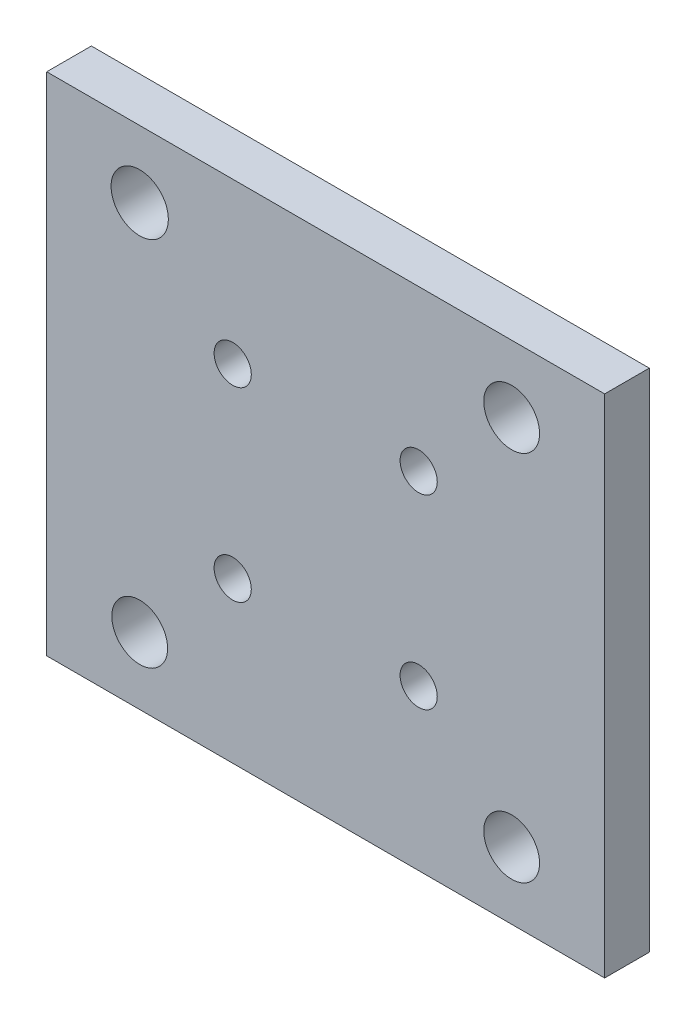
SolidWorks part; units mm, degrees
ref_plane "Front Plane" through (0, 0, 0) normal (0, 0, 1) x (1, 0, 0)
ref_plane "Top Plane" through (0, 0, 0) normal (0, 1, 0) x (1, 0, 0)
ref_plane "Right Plane" through (0, 0, 0) normal (1, 0, 0) x (0, 0, -1)
sketch "Sketch1" plane through (0, 0, 0) normal (0, 0, 1) x (1, 0, 0)
  line L1 (0, 0) -> (75, 0)
  line L2 (0, 0) -> (0, 68)
  line L3 (0, 68) -> (75, 68)
  line L4 (75, 0) -> (75, 68)
  circle A0 centre (12.5, 59) radius 3.85
  circle A1 centre (62.5, 59) radius 3.75
  circle A2 centre (62.5, 9) radius 3.75
  circle A3 centre (12.5, 9) radius 3.75
  circle A4 centre (25, 46.5) radius 2.5
  circle A5 centre (50, 46.5) radius 2.5
  circle A6 centre (50, 21.5) radius 2.5
  circle A7 centre (25, 21.5) radius 2.5
  point P22 (37.5, 0)
  point P23 (37.5, 68)
  point P24 (75, 34)
  point P25 (0, 34)
  dimension "D3" = 50
  dimension "D4" = 50
  dimension "D5" = 50
  dimension "D6" = 50
  dimension "D7" = 12.5
  dimension "D8" = 12.5
  dimension "D9" = 9
  dimension "D10" = 9
  dimension "D11" = 7.5
  dimension "D12" = 7.7
  dimension "D13" = 7.5
  dimension "D14" = 7.5
  dimension "D15" = 5
  dimension "D16" = 5
  dimension "D17" = 5
  dimension "D18" = 5
  dimension "D20" = 25
  dimension "D21" = 12.5
  dimension "D22" = 25
  dimension "D24" = 25
  dimension "D25" = 12.5
  dimension "D26" = 25
  dimension "D1" = 75
  dimension "D2" = 68
  dimension "D19" = 12.5
  dimension "D23" = 12.5
extrude "Boss-Extrude1" add sketch "Sketch1" along normal blind 6
cosmetic thread "Cosmetic Thread1"
cosmetic thread "Cosmetic Thread2"
cosmetic thread "Cosmetic Thread3"
cosmetic thread "Cosmetic Thread4"
